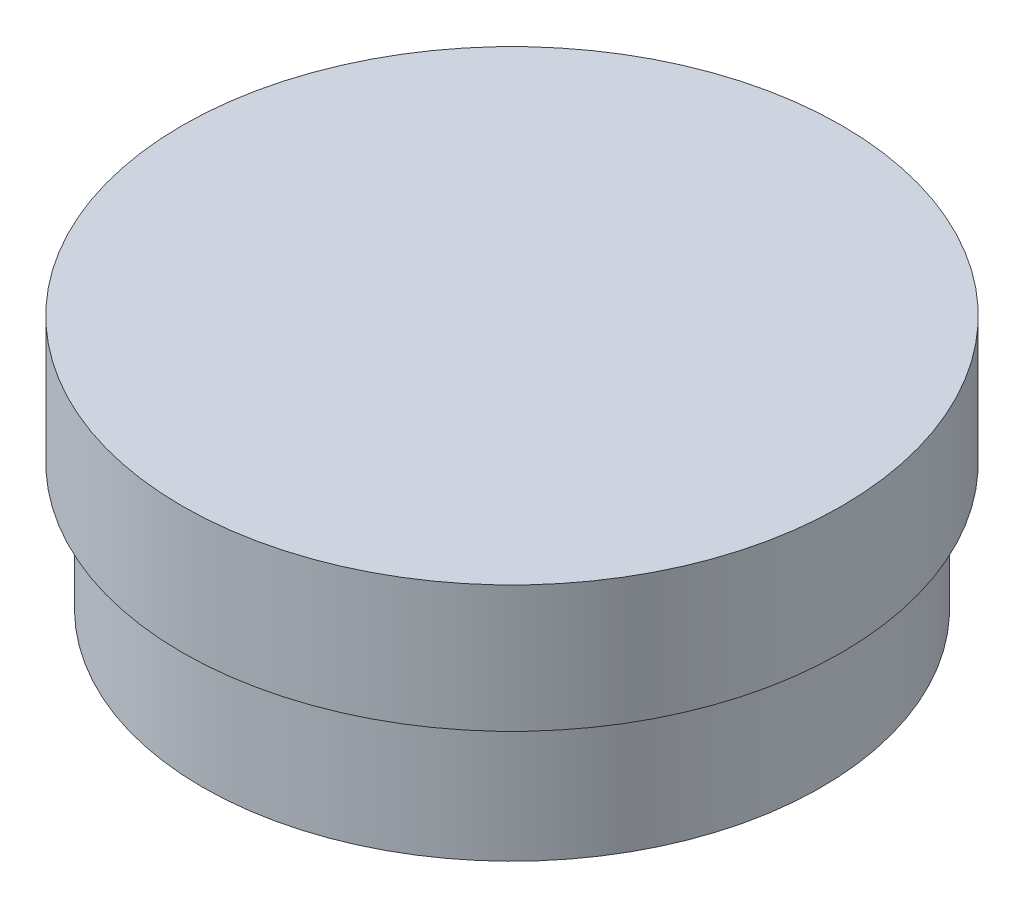
SolidWorks part; units mm, degrees
ref_plane "Front Plane" through (0, 0, 0) normal (0, 0, 1) x (1, 0, 0)
ref_plane "Top Plane" through (0, 0, 0) normal (0, 1, 0) x (1, 0, 0)
ref_plane "Right Plane" through (0, 0, 0) normal (1, 0, 0) x (0, 0, -1)
sketch "Sketch1" plane through (0, 0, 0) normal (0, 0, 1) x (1, 0, 0)
  line L0 (0, 53.1607) -> (0, -48.5179) construction
  line L1 (0, 48.0536) -> (65, 48.0536)
  line L2 (65, 48.0536) -> (65, 23.0536)
  line L3 (65, 23.0536) -> (61, 23.0536)
  line L4 (61, 23.0536) -> (61, -1.9464)
  line L5 (61, -1.9464) -> (0, -1.9464)
  line L6 (0, -1.9464) -> (0, 48.0536)
  dimension "D1" = 65
  dimension "D2" = 25
  dimension "D3" = 25
  dimension "D4" = 4
revolve "Revolve1" add sketch "Sketch1" angle 360 about L0
